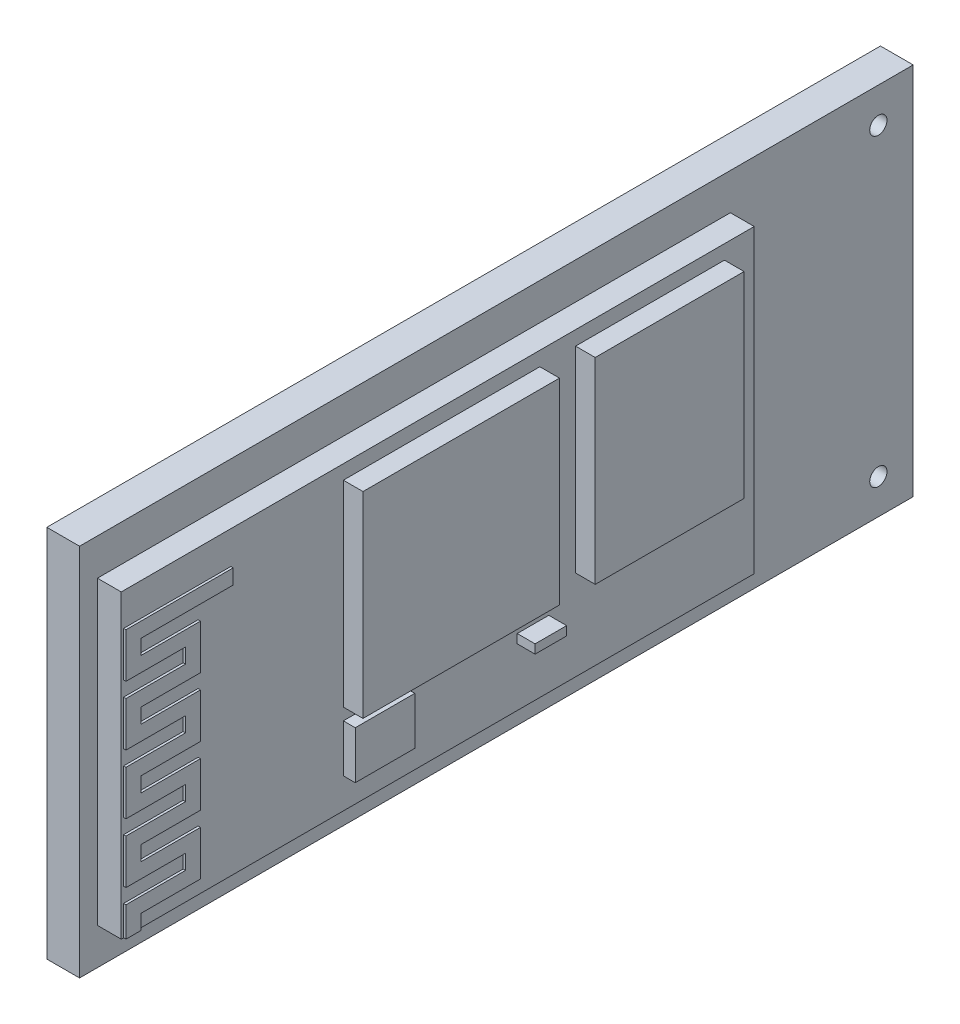
SolidWorks part; units mm, degrees
ref_plane "Front Plane" through (0, 0, 0) normal (0, 0, 1) x (1, 0, 0)
ref_plane "Top Plane" through (0, 0, 0) normal (0, 1, 0) x (1, 0, 0)
ref_plane "Right Plane" through (0, 0, 0) normal (1, 0, 0) x (0, 0, -1)
ref_plane "Plane1" through (-73.7384, 0, 0) normal (1, 0, 0) x (0, 0, -1)
sketch "Sketch1" plane through (-73.7384, 0, 0) normal (1, 0, 0) x (0, 0, -1)
  line L0 (-41.3766, 40.0718) -> (-5.8166, 40.0718)
  line L1 (-5.8166, 40.0718) -> (-5.8166, 56.023)
  line L2 (-5.8166, 56.023) -> (-41.3766, 56.023)
  line L3 (-41.3766, 56.023) -> (-41.3766, 40.0718)
extrude "Boss-Extrude1" add sketch "Sketch1" against normal blind 1.397
sketch "Sketch14" plane through (-73.7384, 0, 0) normal (1, 0, 0) x (0, 0, -1)
  line L0 (-40.6146, 41.6339) -> (-40.6146, 54.4609)
  line L1 (-40.6146, 54.4609) -> (-13.6144, 54.4609)
  line L2 (-13.6144, 54.4609) -> (-13.6144, 41.6339)
  line L3 (-13.6144, 41.6339) -> (-40.6146, 41.6339)
extrude "Boss-Extrude14" add sketch "Sketch14" along normal blind 1.016
sketch "Sketch15" plane through (-72.7224, 0, 0) normal (1, 0, 0) x (0, 0, -1)
  line L0 (-35.941, 41.6339) -> (-40.513, 41.6339)
  line L1 (-40.513, 41.6339) -> (-40.513, 53.0639)
  line L2 (-40.513, 53.0639) -> (-35.941, 53.0639)
  line L3 (-35.941, 53.0639) -> (-35.941, 41.6339)
extrude "Boss-Extrude15" add sketch "Sketch15" along normal blind 0.1016
sketch "Sketch16" plane through (0, 0, 35.941) normal (0, 0, -1) x (-1, 0, 0)
  line L0 (72.6208, 52.4289) -> (72.6208, 41.6339)
  line L1 (72.6208, 41.6339) -> (72.7224, 41.6339)
  line L2 (72.7224, 41.6339) -> (72.7224, 52.4289)
  line L3 (72.7224, 52.4289) -> (72.6208, 52.4289)
extrude "Cut-Extrude1" cut sketch "Sketch16" against normal blind 3.937
sketch "Sketch17" plane through (-72.7224, 0, 0) normal (1, 0, 0) x (0, 0, -1)
  line L0 (-39.878, 42.2689) -> (-39.878, 51.7939)
  line L1 (-39.878, 51.7939) -> (-37.338, 51.7939)
  line L2 (-37.338, 51.7939) -> (-37.338, 42.2689)
  line L3 (-37.338, 42.2689) -> (-39.878, 42.2689)
extrude "Boss-Extrude16" add sketch "Sketch17" along normal blind 0.1016
sketch "Sketch18" plane through (-72.6208, 0, 0) normal (1, 0, 0) x (0, 0, -1)
  line L0 (-37.973, 47.9839) -> (-37.973, 51.1589)
  line L1 (-37.973, 51.1589) -> (-40.513, 51.1589)
  line L2 (-40.513, 51.1589) -> (-40.513, 47.9839)
  line L3 (-40.513, 47.9839) -> (-37.973, 47.9839)
extrude "Cut-Extrude2" cut sketch "Sketch18" against normal blind 0.1016
sketch "Sketch19" plane through (-72.7224, 0, 0) normal (1, 0, 0) x (0, 0, -1)
  line L0 (-37.973, 50.5239) -> (-37.973, 48.6189)
  line L1 (-37.973, 48.6189) -> (-40.513, 48.6189)
  line L2 (-40.513, 48.6189) -> (-40.513, 50.5239)
  line L3 (-40.513, 50.5239) -> (-37.973, 50.5239)
extrude "Boss-Extrude17" add sketch "Sketch19" along normal blind 0.1016
sketch "Sketch20" plane through (-72.6208, 0, 0) normal (1, 0, 0) x (0, 0, -1)
  line L0 (-39.878, 49.8889) -> (-39.878, 49.2539)
  line L1 (-39.878, 49.2539) -> (-37.338, 49.2539)
  line L2 (-37.338, 49.2539) -> (-37.338, 49.8889)
  line L3 (-37.338, 49.8889) -> (-39.878, 49.8889)
extrude "Cut-Extrude3" cut sketch "Sketch20" against normal blind 0.1016
sketch "Sketch21" plane through (-72.6208, 0, 0) normal (1, 0, 0) x (0, 0, -1)
  line L0 (-39.878, 47.3489) -> (-39.878, 46.7139)
  line L1 (-39.878, 46.7139) -> (-37.338, 46.7139)
  line L2 (-37.338, 46.7139) -> (-37.338, 47.3489)
  line L3 (-37.338, 47.3489) -> (-39.878, 47.3489)
extrude "Cut-Extrude4" cut sketch "Sketch21" against normal blind 0.1016
sketch "Sketch22" plane through (-72.6208, 0, 0) normal (1, 0, 0) x (0, 0, -1)
  line L0 (-37.973, 42.9039) -> (-37.973, 46.0789)
  line L1 (-37.973, 46.0789) -> (-40.513, 46.0789)
  line L2 (-40.513, 46.0789) -> (-40.513, 42.9039)
  line L3 (-40.513, 42.9039) -> (-37.973, 42.9039)
extrude "Cut-Extrude5" cut sketch "Sketch22" against normal blind 0.1016
sketch "Sketch23" plane through (-72.7224, 0, 0) normal (1, 0, 0) x (0, 0, -1)
  line L0 (-37.973, 45.4439) -> (-37.973, 43.5389)
  line L1 (-37.973, 43.5389) -> (-40.513, 43.5389)
  line L2 (-40.513, 43.5389) -> (-40.513, 45.4439)
  line L3 (-40.513, 45.4439) -> (-37.973, 45.4439)
extrude "Boss-Extrude18" add sketch "Sketch23" along normal blind 0.1016
sketch "Sketch24" plane through (-72.6208, 0, 0) normal (1, 0, 0) x (0, 0, -1)
  line L0 (-39.878, 44.8089) -> (-39.878, 44.1739)
  line L1 (-39.878, 44.1739) -> (-37.338, 44.1739)
  line L2 (-37.338, 44.1739) -> (-37.338, 44.8089)
  line L3 (-37.338, 44.8089) -> (-39.878, 44.8089)
extrude "Cut-Extrude6" cut sketch "Sketch24" against normal blind 0.1016
sketch "Sketch25" plane through (-72.7224, 0, 0) normal (1, 0, 0) x (0, 0, -1)
  line L0 (-23.7236, 44.0977) -> (-23.7236, 44.4787)
  line L1 (-23.7236, 44.4787) -> (-22.3774, 44.4787)
  line L2 (-22.3774, 44.4787) -> (-22.3774, 44.0977)
  line L3 (-22.3774, 44.0977) -> (-23.7236, 44.0977)
extrude "Boss-Extrude19" add sketch "Sketch25" along normal blind 0.762
sketch "Sketch26" plane through (-72.7224, 0, 0) normal (1, 0, 0) x (0, 0, -1)
  line L0 (-21.2344, 53.8513) -> (-14.8844, 53.8513)
  line L1 (-14.8844, 53.8513) -> (-14.8844, 45.4693)
  line L2 (-14.8844, 45.4693) -> (-21.2344, 45.4693)
  line L3 (-21.2344, 45.4693) -> (-21.2344, 53.8513)
extrude "Boss-Extrude20" add sketch "Sketch26" along normal blind 0.8382
sketch "Sketch27" plane through (-72.7224, 0, 0) normal (1, 0, 0) x (0, 0, -1)
  line L0 (-22.7584, 45.4693) -> (-31.1404, 45.4693)
  line L1 (-31.1404, 45.4693) -> (-31.1404, 53.8513)
  line L2 (-31.1404, 53.8513) -> (-22.7584, 53.8513)
  line L3 (-22.7584, 53.8513) -> (-22.7584, 45.4693)
extrude "Boss-Extrude21" add sketch "Sketch27" along normal blind 0.8382
sketch "Sketch28" plane through (-72.7224, 0, 0) normal (1, 0, 0) x (0, 0, -1)
  line L0 (-31.1404, 42.9293) -> (-31.1404, 44.9613)
  line L1 (-31.1404, 44.9613) -> (-28.6004, 44.9613)
  line L2 (-28.6004, 44.9613) -> (-28.6004, 42.9293)
  line L3 (-28.6004, 42.9293) -> (-31.1404, 42.9293)
extrude "Boss-Extrude22" add sketch "Sketch28" along normal blind 0.508
hole_wizard "Hole1" positions "Sketch34" profile "Sketch33" legacy
sketch "Sketch34" plane through (-75.1354, 0, 0) normal (-1, 0, 0) x (0, 0, 1)
  point P0 (7.3025, 41.5577)
  point P1 (7.3025, 54.5371)
sketch "Sketch33" plane through (-75.1354, 41.5577, 7.3025) normal (0, 1, 0) x (0, 0, 1)
  line L0 (0, 0) -> (0, 3.2512)
  line L1 (0, 3.2512) -> (0.3683, 3.2512)
  line L2 (0.3683, 3.2512) -> (0.3683, 0)
  line L3 (0.3683, 0) -> (0, 0)
  line L4 (0, 110) -> (0, -10) construction
  dimension "Diameter" = 0.7366
  dimension "Depth" = 3.2512
